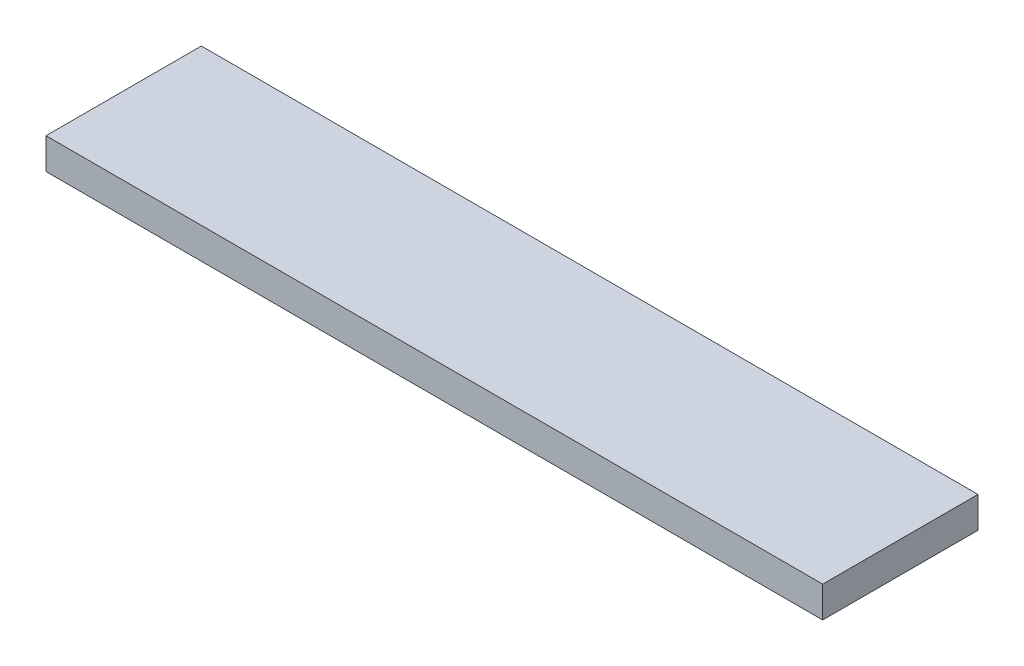
SolidWorks part; units mm, degrees
ref_plane "Front" through (0, 0, 0) normal (0, 0, 1) x (1, 0, 0)
ref_plane "Top" through (0, 0, 0) normal (0, 1, 0) x (1, 0, 0)
ref_plane "Right" through (0, 0, 0) normal (1, 0, 0) x (0, 0, -1)
sketch "Sketch1" plane through (0, 0, 0) normal (0, 1, 0) x (1, 0, 0)
  line L1 (0, 0) -> (250, 0)
  line L2 (0, 0) -> (0, 50)
  line L3 (0, 50) -> (250, 50)
  line L4 (250, 0) -> (250, 50)
  dimension "D1" = 50
  dimension "D2" = 250
extrude "Boss-Extrude1" add sketch "Sketch1" along normal blind 10
